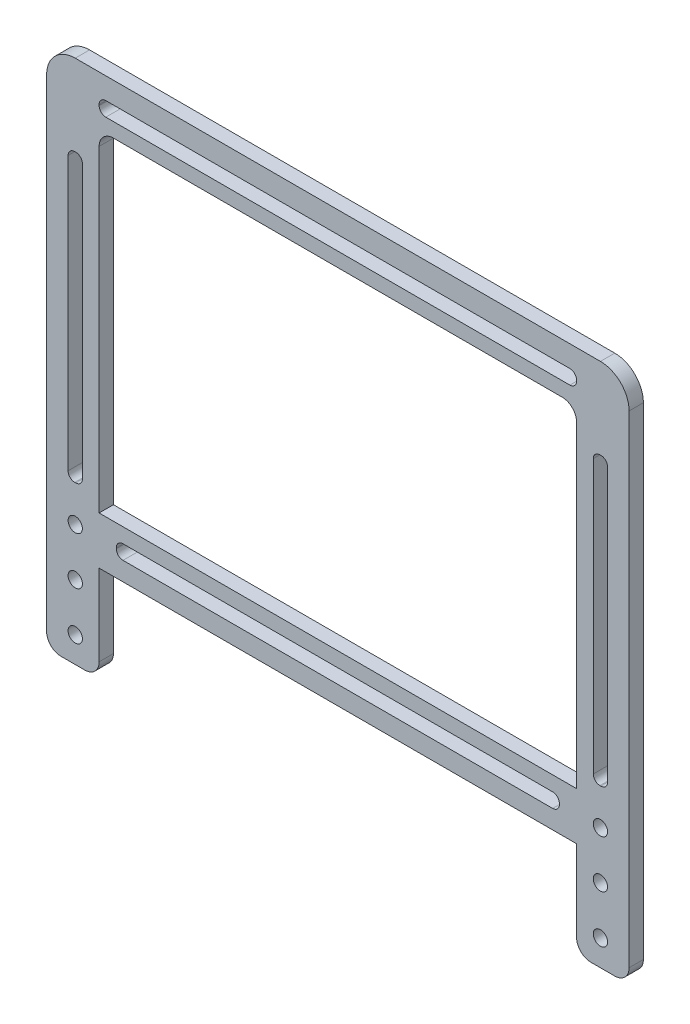
SolidWorks part; units mm, degrees
material "Maple"
ref_plane "Front Plane" through (0, 0, 0) normal (0, 0, 1) x (1, 0, 0)
ref_plane "Top Plane" through (0, 0, 0) normal (0, 1, 0) x (1, 0, 0)
ref_plane "Right Plane" through (0, 0, 0) normal (1, 0, 0) x (0, 0, -1)
sketch "Sketch1" plane through (0, 0, 0) normal (0, 0, 1) x (1, 0, 0)
  line L0 (-55, 55) -> (-55, 49) construction
  line L2 (-61, -52) -> (-61, 49)
  line L3 (-55, 55) -> (55, 55)
  line L4 (61, -52) -> (61, 49)
  line L5 (-61, -55) -> (61, 55) construction
  line L6 (-61, 55) -> (61, -55) construction
  line L7 (-55, -49.5902) -> (55, -49.5902) construction
  line L8 (55, 49) -> (55, 55) construction
  line L9 (-47, 44.5) -> (47, 44.5)
  line L11 (48.6, 50.5) -> (-48.6, 50.5)
  line L12 (50, 49.1) -> (50, 48.9)
  line L13 (48.6, 47.5) -> (-48.6, 47.5)
  line L14 (-50, 49.1) -> (-50, 48.9)
  line L15 (50, 50.5) -> (-50, 47.5) construction
  line L16 (50, 47.5) -> (-50, 50.5) construction
  line L18 (-58, -55) -> (-53, -55)
  line L19 (53, -55) -> (58, -55)
  line L20 (-50, -35) -> (50, -35)
  line L21 (-55.1, 38.0013) -> (-54.9, 38.0013)
  line L22 (-56.5, 36.6013) -> (-56.5, -20.5987)
  line L23 (-55.1, -21.9987) -> (-54.9, -21.9987)
  line L24 (-53.5, 36.6013) -> (-53.5, -20.5987)
  line L25 (-56.5, 38.0013) -> (-53.5, -21.9987) construction
  line L26 (-56.5, -21.9987) -> (-53.5, 38.0013) construction
  line L27 (55.1, 38.0013) -> (54.9, 38.0013)
  line L28 (56.5, 36.6013) -> (56.5, -20.5987)
  line L29 (55.1, -21.9987) -> (54.9, -21.9987)
  line L30 (53.5, 36.6013) -> (53.5, -20.5987)
  line L31 (56.5, 38.0013) -> (53.5, -21.9987) construction
  line L32 (56.5, -21.9987) -> (53.5, 38.0013) construction
  line L33 (-50, -52) -> (-50, -35)
  line L34 (50, -35) -> (50, -52)
  line L35 (-50, 41.5) -> (-50, -25)
  line L36 (-50, -25) -> (50, -25)
  line L37 (50, 41.5) -> (50, -25)
  line L38 (-55, -29.5902) -> (-45, -29.5902) construction
  line L39 (45, -28.0902) -> (-45, -28.0902)
  line L40 (46.4, -29.4902) -> (46.4, -29.6902)
  line L41 (45, -31.0902) -> (-45, -31.0902)
  line L42 (-46.4, -29.4902) -> (-46.4, -29.6902)
  line L43 (46.4, -28.0902) -> (-46.4, -31.0902) construction
  line L44 (46.4, -31.0902) -> (-46.4, -28.0902) construction
  arc A0 (61, 49) -> (55, 55) centre (55, 49) ccw
  arc A1 (-55, 55) -> (-61, 49) centre (-55, 49) ccw
  circle A2 centre (-55, -49.5902) radius 1.5
  circle A3 centre (55, -49.5902) radius 1.5
  circle A4 centre (-55, -39.5902) radius 1.5
  circle A5 centre (-55, -29.5902) radius 1.5
  circle A6 centre (55, -39.5902) radius 1.5
  circle A7 centre (55, -29.5902) radius 1.5
  arc A8 (-48.6, 50.5) -> (-50, 49.1) centre (-48.6, 49.1) ccw
  arc A9 (-50, 48.9) -> (-48.6, 47.5) centre (-48.6, 48.9) ccw
  arc A10 (50, 48.9) -> (48.6, 47.5) centre (48.6, 48.9) cw
  arc A11 (48.6, 50.5) -> (50, 49.1) centre (48.6, 49.1) cw
  arc A12 (-47, 44.5) -> (-50, 41.5) centre (-47, 41.5) ccw
  arc A13 (50, 41.5) -> (47, 44.5) centre (47, 41.5) ccw
  arc A14 (61, -52) -> (58, -55) centre (58, -52) cw
  arc A15 (53, -55) -> (50, -52) centre (53, -52) cw
  arc A16 (-50, -52) -> (-53, -55) centre (-53, -52) cw
  arc A17 (-58, -55) -> (-61, -52) centre (-58, -52) cw
  arc A18 (56.5, 36.6013) -> (55.1, 38.0013) centre (55.1, 36.6013) ccw
  arc A19 (54.9, 38.0013) -> (53.5, 36.6013) centre (54.9, 36.6013) ccw
  arc A20 (56.5, -20.5987) -> (55.1, -21.9987) centre (55.1, -20.5987) cw
  arc A21 (54.9, -21.9987) -> (53.5, -20.5987) centre (54.9, -20.5987) cw
  arc A22 (-53.5, -20.5987) -> (-54.9, -21.9987) centre (-54.9, -20.5987) cw
  arc A23 (-55.1, -21.9987) -> (-56.5, -20.5987) centre (-55.1, -20.5987) cw
  arc A24 (-54.9, 38.0013) -> (-53.5, 36.6013) centre (-54.9, 36.6013) cw
  arc A25 (-55.1, 38.0013) -> (-56.5, 36.6013) centre (-55.1, 36.6013) ccw
  arc A27 (-45, -28.0902) -> (-46.4, -29.4902) centre (-45, -29.4902) ccw
  arc A28 (-46.4, -29.6902) -> (-45, -31.0902) centre (-45, -29.6902) ccw
  arc A29 (46.4, -29.6902) -> (45, -31.0902) centre (45, -29.6902) cw
  arc A30 (45, -28.0902) -> (46.4, -29.4902) centre (45, -29.4902) cw
  point P0 (0, 0)
  point P13 (0, 49)
  point P47 (0, -29.5902)
  point P61 (-55, 8.0013)
  point P66 (55, 8.0013)
  dimension "D3" = 6
  dimension "D8" = 3
  dimension "D9" = 10
  dimension "D14" = 1.4
  dimension "D15" = 3
  dimension "D16" = 10
  dimension "D17" = 3
  dimension "D21" = 1.4
  dimension "D27" = 1.4
  dimension "D1" = 122
  dimension "D2" = 110
  dimension "D4" = 3
  dimension "D5" = 100
  dimension "D6" = 3
  dimension "D7" = 110
  dimension "D10" = 10
  dimension "D11" = 3
  dimension "D12" = 61
  dimension "D13" = 10
  dimension "D18" = 30
  dimension "D19" = 3
  dimension "D20" = 33.0013
  dimension "D22" = 20
  dimension "D23" = 100
  dimension "D24" = 69.5
  dimension "D25" = 11
  dimension "D26" = 11
  dimension "D28" = 3
extrude "Boss-Extrude1" add sketch "Sketch1" along normal blind 3
